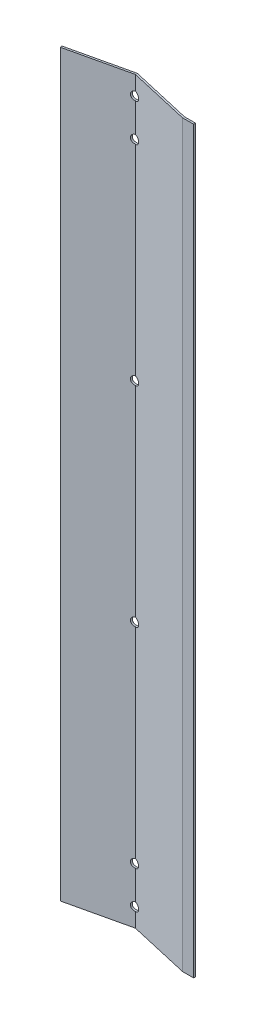
SolidWorks part; units mm, degrees
material "ASTM A36 Steel"
ref_plane "Front Plane" through (0, 0, 0) normal (0, 0, 1) x (1, 0, 0)
ref_plane "Top Plane" through (0, 0, 0) normal (0, 1, 0) x (1, 0, 0)
ref_plane "Right Plane" through (0, 0, 0) normal (1, 0, 0) x (0, 0, -1)
sketch "Sketch1" plane through (0, 0, 0) normal (0, 1, 0) x (1, 0, 0)
  line L0 (-506.6276, -999.7048) -> (-536.6276, -999.7048)
  line L1 (-536.6276, -999.7048) -> (-699.6276, -962.3438)
  line L2 (-699.6276, -962.3438) -> (-862.6276, -999.7048)
  line L3 (-862.6276, -999.7048) -> (-863.6948, -994.82)
  line L4 (-863.6948, -994.82) -> (-699.6276, -957.2258)
  line L5 (-699.6276, -957.2258) -> (-536.0877, -994.7048)
  line L6 (-536.0877, -994.7048) -> (-506.6276, -994.7048)
  line L7 (-506.6276, -994.7048) -> (-506.6276, -999.7048)
extrude "Boss-Extrude1" add sketch "Sketch1" along normal blind 1975
sketch "Sketch2" plane through (0, 0, 994.7048) normal (0, 0, -1) x (-1, 0, 0)
  line L0 (699.6276, 1975) -> (699.6276, 0) construction
  line L1 (699.6276, 1975) -> (863.6948, 1975) construction
  line L2 (699.6276, 0) -> (863.6948, 0) construction
  circle A0 centre (699.6276, 1925) radius 11
  circle A1 centre (699.6276, 1825) radius 11
  circle A2 centre (699.6276, 50) radius 11
  circle A3 centre (699.6276, 150) radius 11
  circle A5 centre (699.6276, 708.333) radius 11
  circle A6 centre (699.6276, 1266.6663) radius 11
  dimension "D1" = 22
  dimension "D2" = 50
  dimension "D3" = 22
  dimension "D4" = 100
  dimension "D5" = 22
  dimension "D6" = 22
  dimension "D7" = 50
  dimension "D8" = 100
  dimension "D9" = 558.333
  dimension "D10" = 22
  dimension "D11" = 558.3333
  dimension "D12" = 22
extrude "Cut-Extrude1" cut sketch "Sketch2" against normal through all both and the other way through all
